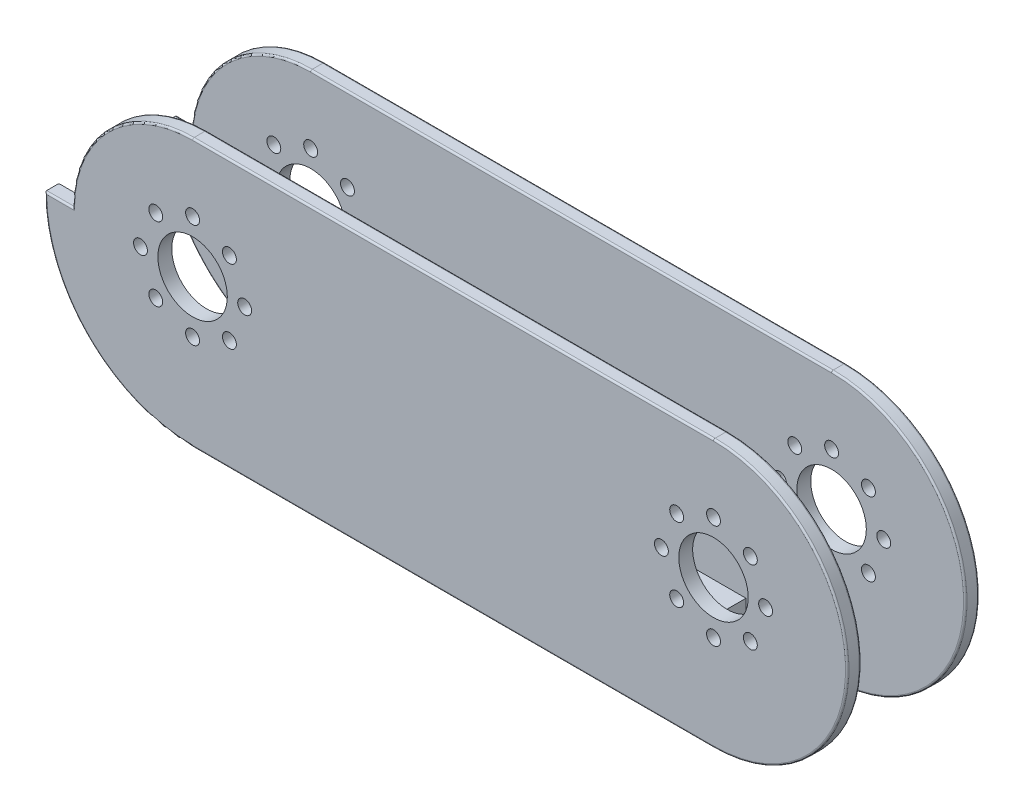
SolidWorks part; units mm, degrees
ref_plane "前视基准面" through (0, 0, 0) normal (0, 0, 1) x (1, 0, 0)
ref_plane "上视基准面" through (0, 0, 0) normal (0, 1, 0) x (1, 0, 0)
ref_plane "右视基准面" through (0, 0, 0) normal (1, 0, 0) x (0, 0, -1)
other "Configuration Table"
sketch "草图1" plane through (0, 0, 0) normal (0, 0, 1) x (1, 0, 0)
  line L0 (-34.5, 0) -> (-42.5, 0)
  line L1 (29.8779, 17.25) -> (38.8418, 17.25)
  line L2 (0, -42.5) -> (150, -42.5)
  line L5 (0, 34.5) -> (150, 34.5)
  arc A1 (-42.5, 0) -> (0, -42.5) centre (0, 0) ccw
  circle A2 centre (0, 0) radius 15 construction
  circle A3 centre (0, 0) radius 10
  arc A7 (-42.5, 0) -> (38.8418, 17.25) centre (0, 0) ccw
  arc A9 (0, 34.5) -> (-34.5, 0) centre (0, 0) ccw
  circle A10 centre (150, 0) radius 10
  arc A11 (150, 34.5) -> (150, -42.5) centre (150, -4) cw
  dimension "D2" = 85
  dimension "D3" = 30
  dimension "D4" = 20
  dimension "D9" = 69
  dimension "D6" = 20
  dimension "D5" = 150
extrude "凸台-拉伸1" add sketch "草图1" along normal mid plane 38
sketch "草图2" plane through (0, 0, 0) normal (0, 0, 1) x (1, 0, 0)
  line L1 (0, -34.5) -> (150, -34.5)
  line L2 (0, 34.5) -> (150, 34.5)
  arc A0 (0, 34.5) -> (0, -34.5) centre (0, 0) ccw
  arc A6 (150, -34.5) -> (150, 34.5) centre (150, 0) ccw
  dimension "D2" = 69
extrude "切除-拉伸2" cut sketch "草图2" against normal mid plane 30
sketch "草图3" plane through (0, 0, 0) normal (0, 0, 1) x (1, 0, 0)
  circle A9 centre (-15, 0) radius 2
  circle A10 centre (-10.6066, 10.6066) radius 2
  circle A11 centre (0, 15) radius 2
  circle A12 centre (10.6066, 10.6066) radius 2
  circle A13 centre (15, 0) radius 2
  circle A14 centre (10.6066, -10.6066) radius 2
  circle A15 centre (0, -15) radius 2
  circle A16 centre (-10.6066, -10.6066) radius 2
  point P20 (0, 0)
  point P23 (0, 0)
  dimension "D1" = 8
  dimension "D2" = 15
  dimension "D3" = 4
extrude "切除-拉伸3" cut sketch "草图3" against normal mid plane 38
sketch "草图4" plane through (0, 0, 0) normal (0, 0, 1) x (1, 0, 0)
  circle A2 centre (135, 0) radius 2
  circle A3 centre (139.3934, 10.6066) radius 2
  circle A4 centre (150, 15) radius 2
  circle A5 centre (160.6066, 10.6066) radius 2
  circle A6 centre (165, 0) radius 2
  circle A7 centre (160.6066, -10.6066) radius 2
  circle A8 centre (150, -15) radius 2
  circle A9 centre (139.3934, -10.6066) radius 2
  point P23 (150, 0)
  dimension "D1" = 15
  dimension "D2" = 4
  dimension "D3" = 8
extrude "切除-拉伸4" cut sketch "草图4" against normal mid plane 38
sketch "草图5" plane through (0, 0, 0) normal (0, 1, 0) x (1, 0, 0)
  line L1 (150, -15) -> (188.5, -15)
  line L2 (188.5, -19) -> (188.5, 19) construction
  line L3 (188.5, -15) -> (188.5, 15)
  line L4 (188.5, 15) -> (150, 15)
  line L5 (150, 15) -> (135, 15)
  line L6 (150, 15) -> (0, 15) construction
  line L7 (135, 15) -> (135, -15)
  line L8 (150, -15) -> (0, -15) construction
  line L9 (135, -15) -> (149.6384, -15)
  line L10 (0, -15) -> (150, -15) construction
  line L11 (149.6384, -15) -> (150, -15)
  dimension "D1" = 15
extrude "切除-拉伸5" cut sketch "草图5" against normal mid plane 85
sketch "草图8" plane through (0, 0, 0) normal (0, 1, 0) x (1, 0, 0)
  line L0 (0, 15) -> (0, -15)
  line L1 (0, -15) -> (-34.5, -15) construction
  line L2 (0, 15) -> (0, -15) construction
  line L3 (0, -15) -> (-42.5, -15)
  line L4 (-42.5, -19) -> (-42.5, 19) construction
  line L5 (-42.5, -15) -> (-42.5, 15)
  line L6 (-42.5, 15) -> (-34.5, 15)
  line L7 (-34.5, 15) -> (0, 15)
extrude "切除-拉伸6" cut sketch "草图8" against normal blind 100
sketch "草图9" plane through (0, 0, 0) normal (0, 1, 0) x (1, 0, 0)
  line L0 (0, 15) -> (0, -15)
  line L1 (0, -15) -> (27.2039, -15)
  line L2 (0, -15) -> (135, -15) construction
  line L3 (27.2039, -15) -> (27.2039, 15)
  line L4 (0, 15) -> (135, 15) construction
  line L5 (27.2039, 15) -> (0, 15)
extrude "切除-拉伸7" cut sketch "草图9" against normal blind 100
sketch "草图10" plane through (0, 0, 0) normal (0, 1, 0) x (1, 0, 0)
  line L0 (135, 15) -> (125.3486, 15)
  line L1 (150, 15) -> (0, 15) construction
  line L2 (125.3486, 15) -> (125.3486, -15)
  line L3 (27.2039, -15) -> (135, -15) construction
  line L4 (125.3486, -15) -> (135, -15)
  line L5 (135, -15) -> (135, 15) construction
  line L6 (135, -15) -> (135, 15)
extrude "切除-拉伸8" cut sketch "草图10" against normal blind 100
fillet "圆角1" radius 0.5 27 edges at (-38.5, 0, -19) (-24.3952, 24.3952, -19) (75, 34.5, -19) (188.5, -4, -19) (75, -42.5, -19) (-30.052, -30.052, -19) (75, -42.5, 19) (188.5, -4, 19) (188.5, -4, 15) (137.6743, -42.5, 15) (188.5, -4, -15) (137.6743, -42.5, -15) (75, 34.5, 19) (-24.3952, 24.3952, 19) (-38.5, 0, -15) (-30.052, -30.052, 15) (-30.052, -30.052, -15) (-38.5, 0, 19) (-24.3952, 24.3952, -15) (75, 34.5, -15) (-24.3952, 24.3952, 15) (27.2039, -42.5, 0) (13.602, -42.5, -15) (13.602, -42.5, 15) (75, 34.5, 15) (125.3486, -42.5, 0) (-30.052, -30.052, 19)
